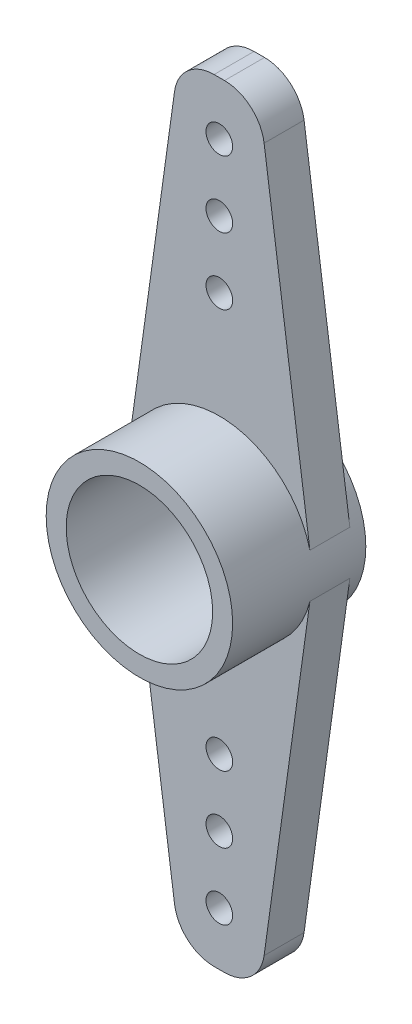
SolidWorks part; units mm, degrees
ref_plane "Front" through (0, 0, 0) normal (0, 0, 1) x (1, 0, 0)
ref_plane "Top" through (0, 0, 0) normal (0, 1, 0) x (1, 0, 0)
ref_plane "Right" through (0, 0, 0) normal (1, 0, 0) x (0, 0, -1)
sketch "Sketch1" plane through (0, 0, 0) normal (0, 0, 1) x (1, 0, 0)
  line L0 (0, 0) -> (0, 33.5454) construction
  line L1 (-0.196, 14.5) -> (0.196, 14.5) construction
  line L2 (-3.4, 0.8307) -> (-1.6818, 13.2063)
  line L3 (3.4, 0.8307) -> (1.6818, 13.2063)
  line L4 (-0.196, 14.5) -> (0.196, 14.5)
  line L5 (-3.5, 0) -> (3.5, 0) construction
  line L6 (-0.196, -14.5) -> (0.196, -14.5) construction
  line L7 (-0.196, -14.5) -> (0.196, -14.5)
  line L8 (3.4, -0.8307) -> (1.6818, -13.2063)
  line L9 (-3.4, -0.8307) -> (-1.6818, -13.2063)
  arc A0 (-3.4, 0.8307) -> (-3.4, -0.8307) centre (0, 0) ccw
  circle A1 centre (0, 10) radius 0.5
  circle A2 centre (0, 12.5) radius 0.5
  circle A3 centre (0, 7.5) radius 0.5
  arc A4 (1.6818, 13.2063) -> (0.196, 14.5) centre (0.196, 13) ccw
  arc A5 (-0.196, 14.5) -> (-1.6818, 13.2063) centre (-0.196, 13) ccw
  circle A6 centre (0, 0) radius 1.5
  arc A7 (-0.196, -14.5) -> (-1.6818, -13.2063) centre (-0.196, -13) cw
  arc A8 (1.6818, -13.2063) -> (0.196, -14.5) centre (0.196, -13) cw
  circle A9 centre (0, -7.5) radius 0.5
  circle A10 centre (0, -12.5) radius 0.5
  circle A11 centre (0, -10) radius 0.5
  arc A12 (3.4, -0.8307) -> (3.4, 0.8307) centre (0, 0) ccw
  dimension "D1" = 7
  dimension "D3" = 1
  dimension "D5" = 1
  dimension "D6" = 1
  dimension "D11" = 1.5
  dimension "D9" = 1.5
  dimension "D12" = 3
  dimension "D2" = 14.5
  dimension "D4" = 10
  dimension "D7" = 2.5
  dimension "D8" = 2.5
  dimension "D10" = 3.4
extrude "Boss-Extrude3" add sketch "Sketch1" along normal blind 1.5
sketch "Sketch2" plane through (0, 0, 1.5) normal (0, 0, 1) x (1, 0, 0)
  circle A0 centre (0, 0) radius 3.5
  dimension "D1" = 7
extrude "Boss-Extrude4" add sketch "Sketch2" along normal blind 3
sketch "Sketch3" plane through (0, 0, 0) normal (0, 0, -1) x (-1, 0, 0)
  circle A0 centre (0, 0) radius 3.5
  circle A4 centre (0, 0) radius 3.25
  dimension "D1" = 7
  dimension "D2" = 0.25
extrude "Boss-Extrude5" add sketch "Sketch3" along normal blind 0.5
sketch "Sketch4" plane through (0, 0, 4.5) normal (0, 0, 1) x (1, 0, 0)
  circle A0 centre (0, 0) radius 2.75
  dimension "D1" = 5.5
extrude "Cut-Extrude1" cut sketch "Sketch4" against normal blind 4
